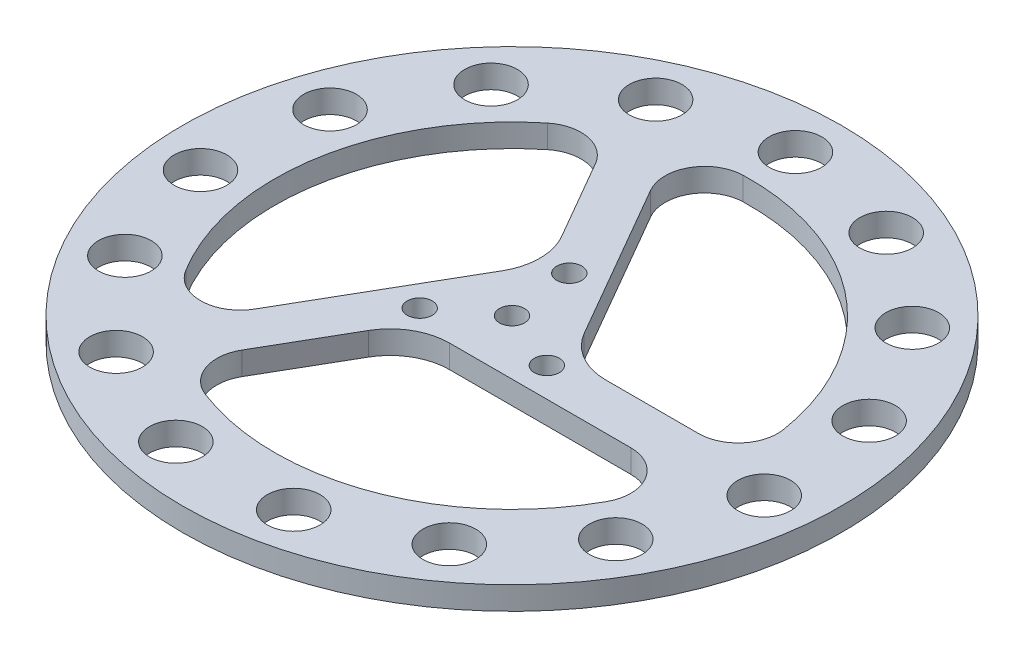
SolidWorks part; units mm, degrees
ref_plane "Front Plane" through (0, 0, 0) normal (0, 0, 1) x (1, 0, 0)
ref_plane "Top Plane" through (0, 0, 0) normal (0, 1, 0) x (1, 0, 0)
ref_plane "Right Plane" through (0, 0, 0) normal (1, 0, 0) x (0, 0, -1)
sketch "Sketch1" plane through (0, 0, 0) normal (0, 1, 0) x (1, 0, 0)
  circle A0 centre (0, 0) radius 50
  circle A1 centre (0, 0) radius 1.9
  dimension "D1" = 100
  dimension "D2" = 3.8
extrude "Boss-Extrude1" add sketch "Sketch1" along normal blind 3.5
sketch "Sketch2" plane through (0, 3.5, 0) normal (0, 1, 0) x (1, 0, 0)
  circle A0 centre (0, 0) radius 43 construction
  circle A1 centre (0, 43) radius 4
  circle A2 centre (0, 0) radius 50 construction
  dimension "D1" = 8
  dimension "D2" = 7
extrude "Cut-Extrude1" cut sketch "Sketch2" against normal up to surface (3.5 mm away) up to face at (0, 0, 50)
pattern_circular "CirPattern1" count 15 over 360 about axis through (0, 0, 0) along (0, 1, 0) of "Cut-Extrude1"
sketch "Sketch3" plane through (0, 3.5, 0) normal (0, 1, 0) x (1, 0, 0)
  line L0 (2.3094, -1.3333) -> (35.9753, -1.3333)
  line L19 (0, 16.6667) -> (-14.4338, -8.3333)
  line L20 (-14.4338, -8.3333) -> (14.4338, -8.3333)
  line L21 (14.4338, -8.3333) -> (0, 16.6667)
  line L22 (0, 2.6667) -> (-2.3094, -1.3333)
  line L23 (-2.3094, -1.3333) -> (2.3094, -1.3333)
  line L24 (2.3094, -1.3333) -> (0, 2.6667)
  line L25 (0, 16.6667) -> (-10.2942, 34.4968)
  circle A2 centre (0, 0) radius 8.3333 construction
  circle A3 centre (0, 0) radius 1.3333 construction
  circle A4 centre (0, 0) radius 36
  circle A6 centre (0, 0) radius 50 construction
  arc A9 (7.7942, 3.1667) -> (15.5885, -1.3333) centre (15.5885, 7.6667) ccw
  arc A10 (29.6348, -1.3333) -> (35.5618, 5.6) centre (29.6348, 4.6667) ccw
  arc A11 (-0.917, 35.9883) -> (-5.9603, 26.9903) centre (-0.7642, 29.9903) ccw
  point P1 (0, -8.3333)
  point P24 (0, 0)
  dimension "D1" = 14
  dimension "D4" = 6
  dimension "D5" = 9
  dimension "D2" = 25
  dimension "D3" = 7
extrude "Cut-Extrude5" cut sketch "Sketch3" against normal blind 10
pattern_circular "CirPattern3" count 3 over 360 about axis through (0, 0, 0) along (0, 1, 0) of "Cut-Extrude5"
sketch "Sketch4" plane through (0, 0, 0) normal (0, 1, 0) x (1, 0, 0)
  line L0 (-10.1511, 20.2489) -> (-4.0889, 23.7489) construction
  line L4 (-6.6395, 14.1667) -> (-13.6627, 26.3312) construction
  line L5 (7.7942, 3.1667) -> (-5.9603, 26.9903) construction
  line L6 (-7.12, 21.9989) -> (1.0945, 5.1567) construction
  circle A0 centre (0, 0) radius 10 construction
  circle A1 centre (-1.2307, 9.924) radius 1.9
  circle A2 centre (9.1831, -3.8992) radius 1.9
  circle A3 centre (-7.995, -6.0062) radius 1.9
  point P12 (-1.2307, 9.924)
  point P15 (-2.3796, 10.7395)
  point P16 (-0.7548, 10.9741)
  point P17 (-1.0993, 9.9394)
  point P22 (-0.0142, 0.0062)
  dimension "D1" = 3.8
  dimension "D3" = 10
  dimension "D4" = 86
  dimension "D2" = 3
extrude "Cut-Extrude6" cut sketch "Sketch4" along normal up to surface (3.5 mm away) up to face at (-17.9756, 3.5, -6.1448)
